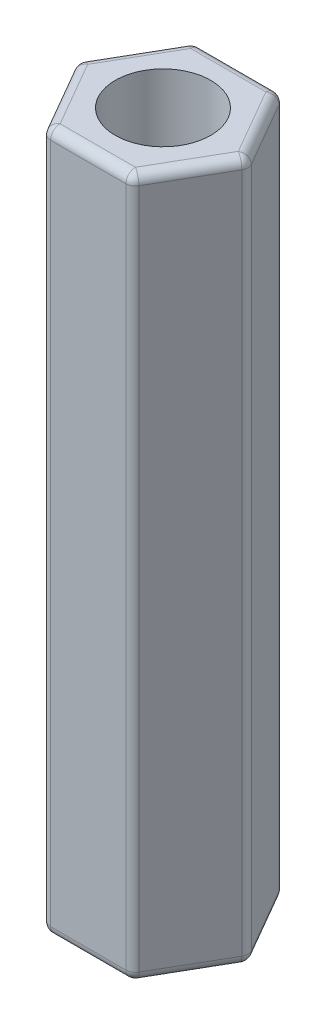
SolidWorks part; units mm, degrees
ref_plane "前视基准面" through (0, 0, 0) normal (0, 0, 1) x (1, 0, 0)
ref_plane "上视基准面" through (0, 0, 0) normal (0, 1, 0) x (1, 0, 0)
ref_plane "右视基准面" through (0, 0, 0) normal (1, 0, 0) x (0, 0, -1)
sketch "草图1" plane through (0, 0, 0) normal (0, 1, 0) x (1, 0, 0)
  line L1 (2.7135, 0) -> (1.3568, 2.35)
  line L2 (1.3568, 2.35) -> (-1.3568, 2.35)
  line L3 (-1.3568, 2.35) -> (-2.7135, 0)
  line L4 (-2.7135, 0) -> (-1.3568, -2.35)
  line L5 (-1.3568, -2.35) -> (1.3568, -2.35)
  line L6 (1.3568, -2.35) -> (2.7135, 0)
  circle A0 centre (0, 0) radius 2.35 construction
  circle A1 centre (0, 0) radius 1.5
  dimension "D1" = 4.7
extrude "凸台-拉伸1" add sketch "草图1" along normal blind 22
fillet "圆角1" radius 0.3 18 edges at (2.7135, 11, 0) (1.3568, 11, -2.35) (-1.3568, 11, -2.35) (-2.7135, 11, 0) (-1.3568, 11, 2.35) (1.3568, 11, 2.35) (0, 22, 2.35) (-2.0352, 22, 1.175) (-2.0352, 22, -1.175) (0, 22, -2.35) (2.0352, 22, -1.175) (2.0352, 22, 1.175) (0, 0, 2.35) (-2.0352, 0, 1.175) (-2.0352, 0, -1.175) (0, 0, -2.35) (2.0352, 0, -1.175) (2.0352, 0, 1.175)
